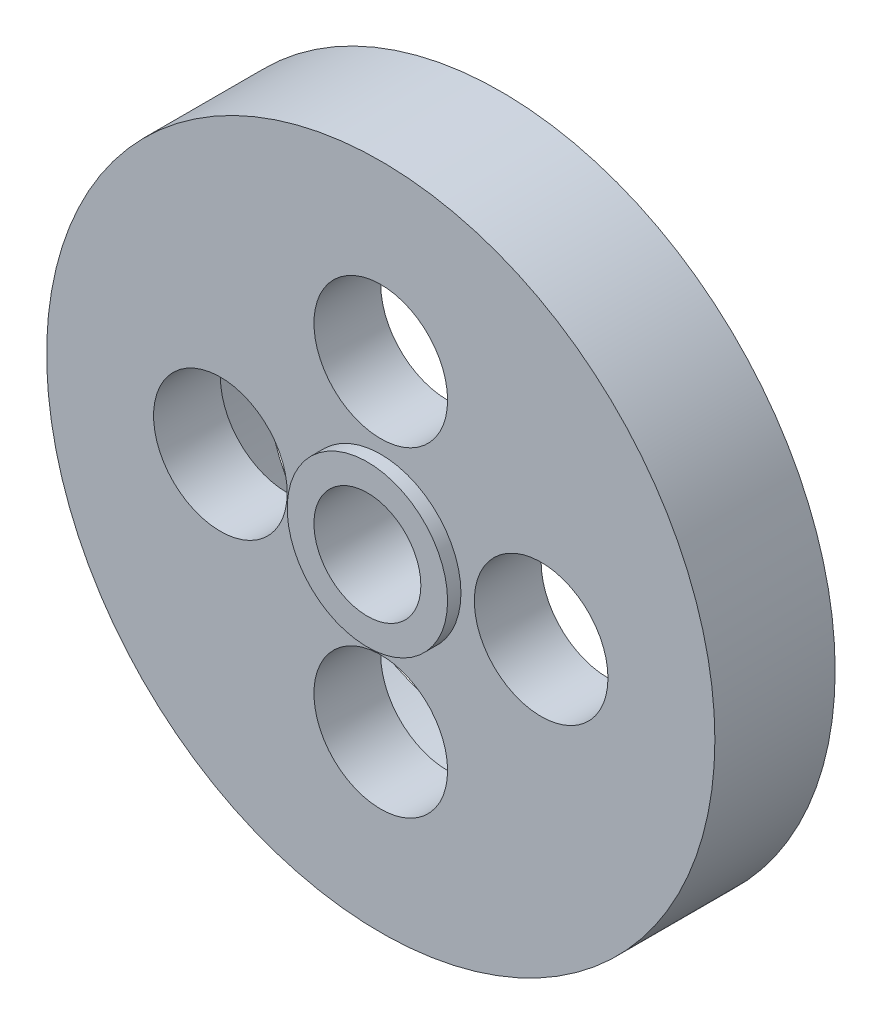
SolidWorks part; units mm, degrees
ref_plane "Front Plane" through (0, 0, 0) normal (0, 0, 1) x (1, 0, 0)
ref_plane "Top Plane" through (0, 0, 0) normal (0, 1, 0) x (1, 0, 0)
ref_plane "Right Plane" through (0, 0, 0) normal (1, 0, 0) x (0, 0, -1)
sketch "Sketch1" plane through (0, 0, 0) normal (0, 0, 1) x (1, 0, 0)
  circle A0 centre (0, 0) radius 25
  circle A1 centre (0, 0) radius 12 construction
  circle A2 centre (0, 0) radius 4
  circle A3 centre (0, 12) radius 5
  circle A4 centre (12, 0) radius 5
  circle A5 centre (0, -12) radius 5
  circle A6 centre (-12, 0) radius 5
  point P7 (0, 0)
  point P16 (0, 0)
  dimension "D1" = 50
  dimension "D2" = 24
  dimension "D3" = 8
  dimension "D4" = 10
  dimension "D5" = 4
extrude "Boss-Extrude1" add sketch "Sketch1" against normal blind 9
sketch "Sketch2" plane through (0, 0, -9) normal (0, 0, -1) x (-1, 0, 0)
  circle A0 centre (0, 0) radius 18
  dimension "D1" = 36
extrude "Cut-Extrude1" cut sketch "Sketch2" against normal blind 4
sketch "Sketch3" plane through (0, 0, 0) normal (0, 0, 1) x (1, 0, 0)
  circle A0 centre (0, 0) radius 6
  circle A1 centre (0, 0) radius 4
  dimension "D1" = 12
  dimension "D2" = 8
extrude "Boss-Extrude2" add sketch "Sketch3" along normal blind 1
sketch "Sketch5" plane through (0, 0, -5) normal (0, 0, -1) x (-1, 0, 0)
  circle A0 centre (0, 0) radius 6
extrude "Cut-Extrude2" cut sketch "Sketch5" against normal blind 1
sketch "Sketch6" plane through (0, 0, -4) normal (0, 0, -1) x (-1, 0, 0)
  circle A0 centre (0, 0) radius 6
  circle A1 centre (0, 0) radius 4
extrude "Boss-Extrude3" add sketch "Sketch6" along normal blind 1
